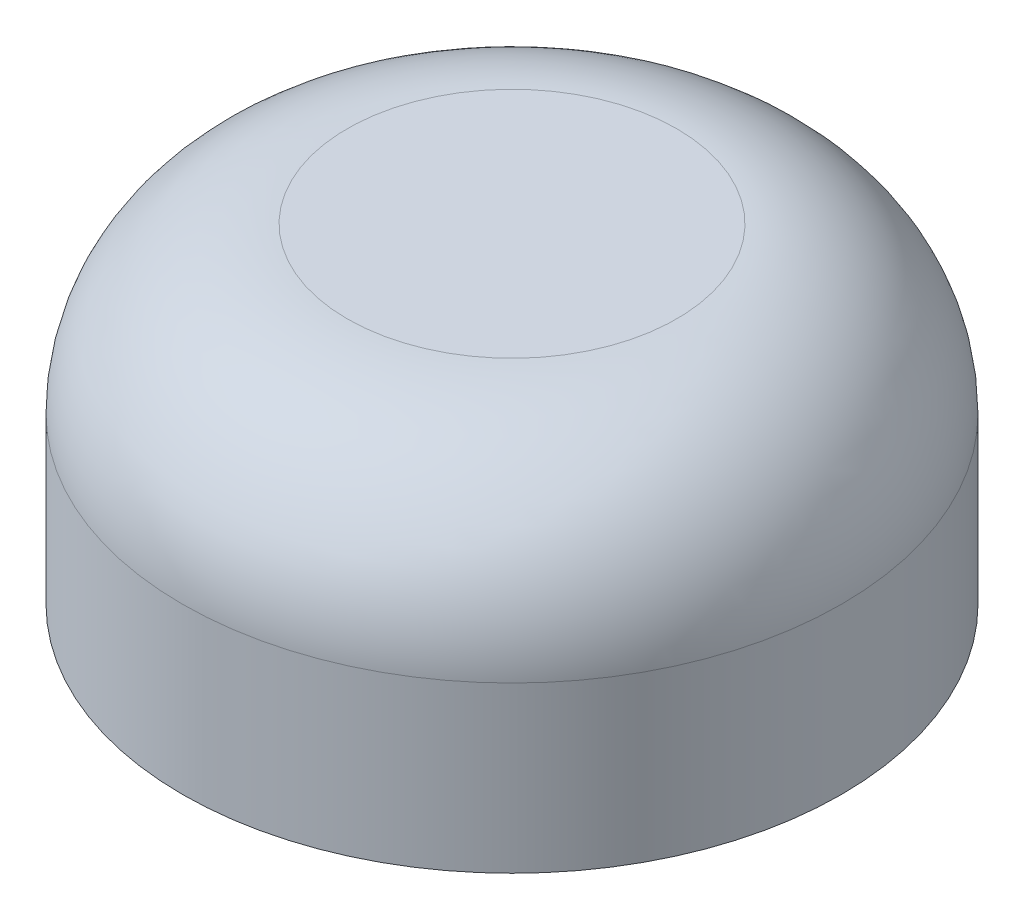
SolidWorks part; units mm, degrees
material "Nylon 6/10"
ref_plane "Front Plane" through (0, 0, 0) normal (0, 0, 1) x (1, 0, 0)
ref_plane "Top Plane" through (0, 0, 0) normal (0, 1, 0) x (1, 0, 0)
ref_plane "Right Plane" through (0, 0, 0) normal (1, 0, 0) x (0, 0, -1)
sketch "Sketch1" plane through (0, 0, 0) normal (0, 1, 0) x (1, 0, 0)
  circle A0 centre (0, 0) radius 6.35
  dimension "D1" = 12.7
extrude "Boss-Extrude1" add sketch "Sketch1" along normal blind 6.35
sketch "Sketch2" plane through (0, 0, 0) normal (0, -1, 0) x (1, 0, 0)
  circle A0 centre (0, 0) radius 3.175
  dimension "D1" = 6.35
extrude "Cut-Extrude1" cut sketch "Sketch2" against normal blind 3.556
fillet "Fillet1" radius 3.175 1 edges at (0, 6.35, 6.35)
